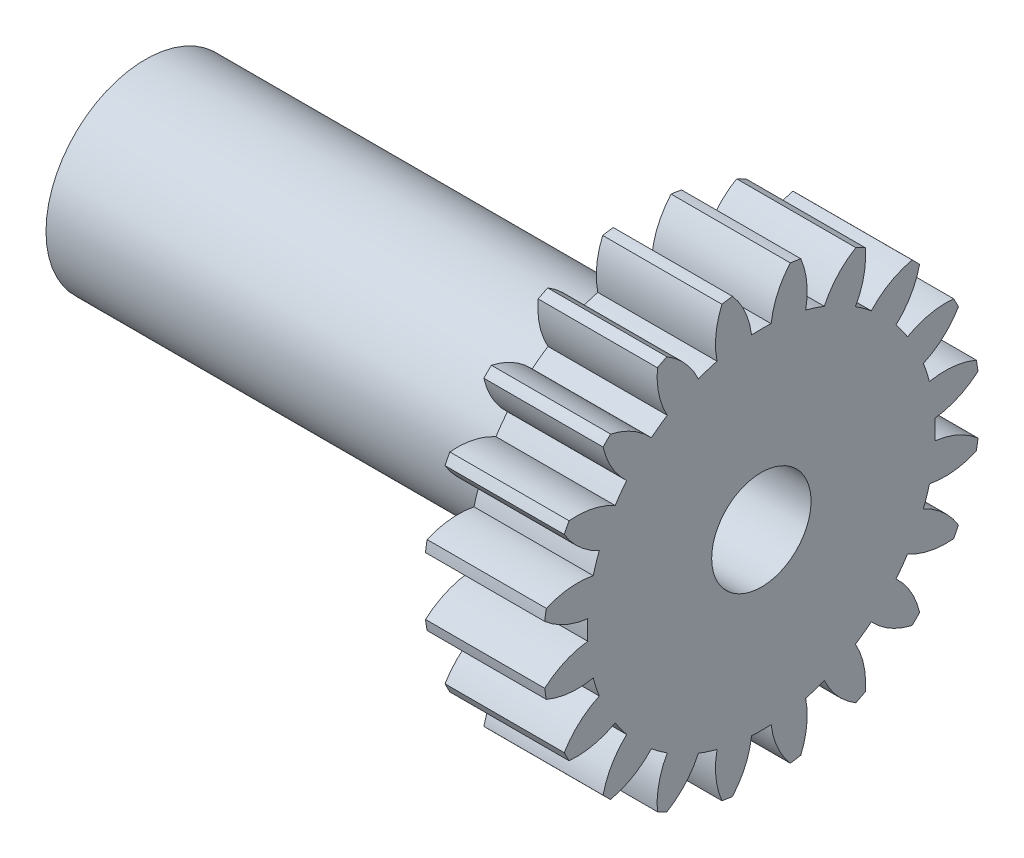
SolidWorks part; units mm, degrees
ref_plane "Plane1" through (0, 0, 0) normal (0, 0, 1) x (1, 0, 0)
ref_plane "Plane2" through (0, 0, 0) normal (0, 1, 0) x (1, 0, 0)
ref_plane "Plane3" through (0, 0, 0) normal (1, 0, 0) x (0, 0, -1)
sketch "HoldingSke" plane through (0, 0, 0) normal (0, 1, 0) x (1, 0, 0)
  line L0 (0, 0) -> (0.4698, -0.171)
  line L1 (-15, 0) -> (100, 0) construction
  line L2 (0, 0) -> (-2.1039, 2.3779)
  line L3 (0, 0) -> (-11.863, 4.5341)
  line L4 (0, 0) -> (8.1152, 2.9537)
  line L5 (0, 0) -> (-46.8476, -17.4728)
  line L6 (0, 0) -> (-9.9476, -6.7116)
  line L7 (-2.1039, 2.3779) -> (8.6586, 51.2059)
  line L8 (-76.2, 54.61) -> (-74.4, 54.61)
  line L9 (-71.009, 38.7566) -> (-53.1078, 45.2721)
  line L10 (-76.2, 71.12) -> (104.1128, 71.12)
  line L11 (0, 0) -> (-12, 0)
  line L12 (-76.2, 101.6) -> (-76.133, 101.6)
  line L13 (24.9733, 27.94) -> (52.9518, 28.4284)
  line L14 (24.9733, 27.94) -> (24.9743, 27.94)
  line L15 (24.9733, 27.94) -> (100.4006, 29.5858)
  line L16 (-63.627, -2) -> (-12.827, -2)
  circle A0 centre (0, 0) radius 5
  circle A1 centre (0, 0) radius 17.499
  circle A2 centre (0, 0) radius 37.5
  circle A3 centre (0, 0) radius 5
  dimension "MHD" = 34.998
  dimension "Hub_dia" = 75
  dimension "Bore" = 10
  dimension "MBD" = 10
  dimension "Num_teeth" = 20
  dimension "Pitch" = 0.5
  dimension "Overall_len" = 50
  dimension "Show_teeth" = 20
  dimension "Thickness" = 12
  dimension "OAL" = 50.0001
  dimension "T_dim" = 1.8
  dimension "Ap" = 20
  dimension "H" = 19.05
  dimension "Pitch_radius" = 180.3128
  dimension "Width" = 12
  dimension "Backlash" = 0.067
  dimension "Addendum_fac" = 1
  dimension "Dedendum_fac" = 1.25
  dimension "Clearance_fac" = 0.25
  dimension "Dedendum_add" = 0.001
  dimension "Module" = 2
sketch "BasProSke" plane through (0, 0, 0) normal (0, 1, 0) x (1, 0, 0)
  line L0 (-10, 0) -> (60, 0) construction
  line L1 (0, 0) -> (0, 22)
  line L2 (0, 0) -> (12, 0)
  line L3 (12, 0) -> (12, 22)
  line L4 (12, 22) -> (0, 22)
  dimension "Thickness" = 12
  dimension "Diameter" = 44
revolve "Base-Revolve" add sketch "BasProSke" angle 360 about L0
sketch "TooCutSke" plane through (0, 0, 0) normal (1, 0, 0) x (0, 0, -1)
  line L1 (0, 0) -> (0, 107) construction
  line L2 (0, 0) -> (-1.6864, 19.9288) construction
  line L3 (0, 0) -> (-6.2409, 39.4033) construction
  line L4 (-1.6864, 19.9288) -> (-3.1204, 19.7016) construction
  arc A0 (0.9862, 17.4712) -> (-0.9862, 17.4712) centre (0, 0) ccw
  arc A1 (2.9329, 21.8293) -> (-2.9329, 21.8293) centre (0, 0) ccw
  circle A2 centre (0, 0) radius 20 construction
  circle A3 centre (0, 0) radius 18.7939 construction
  arc A4 (-0.9862, 17.4712) -> (-2.9329, 21.8293) centre (-8.9313, 16.536) ccw
  arc A5 (2.9329, 21.8293) -> (0.9862, 17.4712) centre (8.9313, 16.536) ccw
  dimension "Root_dia" = 34.998
  dimension "Overcut_dia" = 44.0508
  dimension "Pitch_dia" = 40
  dimension "Base_dia" = 37.5877
  dimension "Flank_rad" = 8
  dimension "Half_ang" = 9
  dimension "Half_CT" = 1.4519
extrude "ToothCut" cut sketch "TooCutSke" along normal through all
fillet "Breaks" [suppressed] radius 0.04
fillet "RootFillets" [suppressed] radius 0.501
pattern_circular "TeethCuts" count 20 every 18 about axis through (-10, 0, 0) along (1, 0, 0) of "ToothCut", "RootFillets", "Breaks"
sketch "HubNeaOneSke" plane through (0, 0, 0) normal (-1, 0, 0) x (0, 0, 1)
  circle A0 centre (0, 0) radius 17.499
  dimension "Diameter" = 34.998
extrude "HubNearOne" [suppressed] add sketch "HubNeaOneSke" along normal blind 38.0001
sketch "HubNeaBotSke" plane through (0, 0, 0) normal (-1, 0, 0) x (0, 0, 1)
  circle A0 centre (0, 0) radius 17.499
  dimension "Diameter" = 34.998
extrude "HubNearBoth" [suppressed] add sketch "HubNeaBotSke" along normal blind 19
ref_plane "FarPln" through (12, 0, 0) normal (1, 0, 0) x (0, 0, -1)
sketch "HubFarSke" plane through (12, 0, 0) normal (1, 0, 0) x (0, 0, -1)
  circle A0 centre (0, 0) radius 17.499
  dimension "Diameter" = 34.998
extrude "HubFar" [suppressed] add sketch "HubFarSke" along normal blind 19
sketch "BorSke" plane through (0, 0, 0) normal (1, 0, 0) x (0, 0, -1)
  circle A0 centre (0, 0) radius 5
  dimension "Diameter" = 10
extrude "Bore" cut sketch "BorSke" along normal mid plane 100.0001
sketch "KeySke" plane through (0, 0, 0) normal (1, 0, 0) x (0, 0, -1)
  line L0 (-1.5, 0) -> (-1.5, 6.8)
  line L1 (-1.5, 6.8) -> (1.5, 6.8)
  line L2 (1.5, 6.8) -> (1.5, 0)
  line L3 (0, 0) -> (0, 34) construction
  line L4 (-1.5, 0) -> (1.5, 0)
  dimension "Offset" = 6.8
  dimension "Width" = 3
extrude "Keyway" [suppressed] cut sketch "KeySke" along normal mid plane 100.0001
pattern_circular "Keyway2" [suppressed] count 2 every 90 about axis through (-10, 0, 0) along (1, 0, 0)
sketch "Sketch1" plane through (0, 0, 0) normal (-1, 0, 0) x (0, 0, 1)
  circle A0 centre (0, 0) radius 10
  circle A2 centre (0, 0) radius 5
  point P16 (0, 0)
extrude "Boss-Extrude1" add sketch "Sketch1" along normal blind 50
equation "' \"Module@HoldingSke\" = 6.35"
equation "' \"Num_teeth@HoldingSke\" = 12"
equation "' \"Ap@HoldingSke\" =  20"
equation "' \"Ap@HoldingSke\" = 20"
equation "' \"Width@HoldingSke\" = 0.5 * 25.4"
equation "' \"Hub_dia@HoldingSke\"= 1 * 25.4"
equation "' \"Hub_dia@HoldingSke\" = 1 * 25.4"
equation "' \"Overall_len@HoldingSke\" = 1.0 * 25.4"
equation "' \"Bore@HoldingSke\" = 0.75 * 25.4"
equation "' \"T_dim@HoldingSke\" = 0.1 * 25.4"
equation "' \"Width@KeySke\" = 0.25 * 25.4"
equation "' \"Show_teeth@HoldingSke\" = 13"
equation "' \"Backlash@HoldingSke\" = 0.009 * 25.4"
equation "' \"Addendum_fac@HoldingSke\" = 1.0"
equation "' \"Dedendum_fac@HoldingSke\" = 1.25"
equation "' \"Dedendum_add@HoldingSke\" = 0.00005 * 25.4"
equation "' \"Clearance_fac@HoldingSke\" = 0.25"
equation "\"Pitch@HoldingSke\" = 1 / \"Module@HoldingSke\""
equation "\"Overcut_dia@TooCutSke\" = (\"Num_teeth@HoldingSke\" + 2 * \"Addendum_fac@HoldingSke\") / \"Pitch@HoldingSke\" + 0.002 * 25.4"
equation "\"Pitch_dia@TooCutSke\" = \"Num_teeth@HoldingSke\" / \"Pitch@HoldingSke\""
equation "\"Base_dia@TooCutSke\" = \"Num_teeth@HoldingSke\" / \"Pitch@HoldingSke\" * cos((\"Ap@HoldingSke\"  * 3.14159265 / 180))"
equation "\"Root_dia@TooCutSke\" = (\"Num_teeth@HoldingSke\" + 2) / \"Pitch@HoldingSke\" - 2 * (\"Addendum_fac@HoldingSke\" + \"Dedendum_fac@HoldingSke\") / \"Pitch@HoldingSke\" - \"Dedendum_add@HoldingSke\" * 2"
equation "\"Half_ang@TooCutSke\" = 180 / \"Num_teeth@HoldingSke\""
equation "\"Half_CT@TooCutSke\" = \"Num_teeth@HoldingSke\" / \"Pitch@HoldingSke\" * sin((3.14159265 / 2 / \"Num_teeth@HoldingSke\")) / 2 - 7 * \"Backlash@HoldingSke\" / 4"
equation "\"Flank_rad@TooCutSke\" = \"Num_teeth@HoldingSke\" / \"Pitch@HoldingSke\" / 5"
equation "\"Radius@RootFillets\" = \"Clearance_fac@HoldingSke\" / \"Pitch@HoldingSke\" + \"Dedendum_add@HoldingSke\""
equation "\"Break_rad@Breaks\" = 0.02 / \"Pitch@HoldingSke\""
equation "\"Thickness@HoldingSke\" = \"Width@HoldingSke\""
equation "\"OAL@HoldingSke\" = \"Thickness@HoldingSke\""
equation "\"MHD@HoldingSke\" = (\"Num_teeth@HoldingSke\" + 2) / \"Pitch@HoldingSke\" - 2 * (\"Addendum_fac@HoldingSke\" + \"Dedendum_fac@HoldingSke\")  / \"Pitch@HoldingSke\" - \"Dedendum_add@HoldingSke\" * 2"
equation "\"MBD@HoldingSke\" = (\"Num_teeth@HoldingSke\" + 2) / \"Pitch@HoldingSke\" - 2 * (\"Addendum_fac@HoldingSke\" + \"Dedendum_fac@HoldingSke\")  / \"Pitch@HoldingSke\" - \"Dedendum_add@HoldingSke\" * 2 - 0.002 * 25.4"
equation "\"MHD@HoldingSke\" = ((sgn( \"MHD@HoldingSke\" - \"Hub_dia@HoldingSke\" )-1)*( \"MHD@HoldingSke\" - \"Hub_dia@HoldingSke\" ))/-2+ \"Hub_dia@HoldingSke\""
equation "\"MBD@HoldingSke\" = ((sgn( \"MBD@HoldingSke\" - \"Bore@HoldingSke\" )-1)*( \"MBD@HoldingSke\" - \"Bore@HoldingSke\" ))/-2+ \"Bore@HoldingSke\""
equation "\"OAL@HoldingSke\" = ((sgn( \"OAL@HoldingSke\" - \"Overall_len@HoldingSke\" )+1)*( \"OAL@HoldingSke\" - \"Overall_len@HoldingSke\" ))/2 + \"Overall_len@HoldingSke\" + 0.000002 * 25.4"
equation "\"Num_teeth@TeethCuts\" = int( \"Show_teeth@HoldingSke\" ) + 1"
equation "\"Num_teeth@TeethCuts\" = ((sgn( \"Num_teeth@TeethCuts\" - \"Num_teeth@HoldingSke\" )-1)*( \"Num_teeth@TeethCuts\" - \"Num_teeth@HoldingSke\" ))/-2+ \"Num_teeth@HoldingSke\""
equation "\"Num_teeth@TeethCuts\" = ((sgn( \"Num_teeth@TeethCuts\" - 2.0)+1)*( \"Num_teeth@TeethCuts\" - 2.0))/2 +2.0"
equation "\"Angle@TeethCuts\" = 360.0 / \"Num_teeth@HoldingSke\""
equation "\"Diameter@BasProSke\" = (\"Num_teeth@HoldingSke\" + 2 * \"Addendum_fac@HoldingSke\") / \"Pitch@HoldingSke\""
equation "\"Thickness@BasProSke\"  = \"Thickness@HoldingSke\""
equation "' \"Fillet_rad@BasProSke\" =  \"Thickness@HoldingSke\" * 0.05"
equation "' \"Fillet_rad@BasProSke\" = \"Thickness@HoldingSke\" * 0.05"
equation "\"MHD@HoldingSke\" = ((sgn( \"MHD@HoldingSke\" - \"Root_dia@TooCutSke\" )-1)*( \"MHD@HoldingSke\" - \"Root_dia@TooCutSke\" ))/-2+ \"Root_dia@TooCutSke\""
equation "\"Diameter@HubNeaOneSke\" = \"MHD@HoldingSke\""
equation "\"Length@HubNearOne\" = \"OAL@HoldingSke\" - \"Thickness@BasProSke\""
equation "\"Diameter@HubNeaBotSke\" = \"MHD@HoldingSke\""
equation "\"Length@HubNearBoth\" = ( \"OAL@HoldingSke\" - \"Thickness@BasProSke\" ) / 2.0"
equation "\"Thickness@FarPln\" = \"Thickness@BasProSke\""
equation "\"Diameter@HubFarSke\" = \"MHD@HoldingSke\""
equation "\"Length@HubFar\" = ( \"OAL@HoldingSke\" - \"Thickness@BasProSke\" ) / 2.0"
equation "\"Diameter@BorSke\" = \"MBD@HoldingSke\""
equation "\"D1@Bore\" = \"OAL@HoldingSke\" * 2.0"
equation "\"D1@Keyway\" = \"OAL@HoldingSke\" * 2.0"
equation "\"Offset@KeySke\" = \"T_dim@HoldingSke\" + \"MBD@HoldingSke\" / 2.0"
